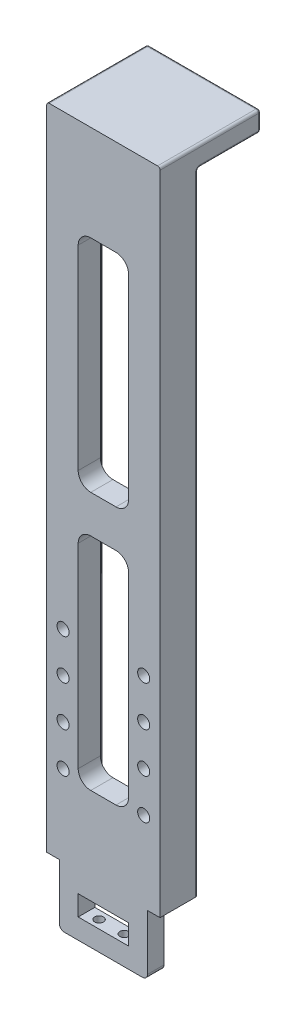
SolidWorks part; units mm, degrees
ref_plane "Ebene vorne" through (0, 0, 0) normal (0, 0, 1) x (1, 0, 0)
ref_plane "Ebene oben" through (0, 0, 0) normal (0, 1, 0) x (1, 0, 0)
ref_plane "Ebene rechts" through (0, 0, 0) normal (1, 0, 0) x (0, 0, -1)
sketch "Skizze1" plane through (0, 0, 0) normal (0, 1, 0) x (1, 0, 0)
  line L0 (-32.248, 0) -> (72.9564, 0) construction
  line L1 (-22.5, 7.5) -> (22.5, 7.5)
  line L2 (-22.5, 7.5) -> (-22.5, -7.5)
  line L3 (-22.5, -7.5) -> (22.5, -7.5)
  line L4 (22.5, 7.5) -> (22.5, -7.5)
  line L5 (0, 40.3012) -> (0, -36.3862) construction
  circle A0 centre (0, 34) radius 32.7
  dimension "D3" = 65.4
  dimension "D1" = 45
  dimension "D2" = 15
  dimension "D4" = 34
extrude "Rundung" add sketch "Skizze1" along normal blind 250 contours A0 L1 L2 L3 L4
sketch "Skizze2" plane through (0, 250, 0) normal (0, 1, 0) x (1, 0, 0)
  line L0 (0, 0) -> (0, 7.7395) construction
  line L1 (-11, 4.5707) -> (11, 4.5707)
  line L2 (-11, 4.5707) -> (-11, 1.3)
  line L3 (-11, 1.3) -> (11, 1.3)
  line L4 (11, 4.5707) -> (11, 1.3)
  line L5 (0, 7.7395) -> (0, -13.5524) construction
  arc A0 (-19.1583, 7.5) -> (19.1583, 7.5) centre (0, 34) ccw construction
  point P7 (0, 1.3)
  dimension "D1" = 22
extrude "AussparungLauf" cut sketch "Skizze2" against normal through all
sketch "Skizze4" plane through (0, 0, -1.3) normal (0, 0, -1) x (-1, 0, 0)
  line L0 (0, 0) -> (0, 250) construction
  line L1 (11, 250) -> (-11, 250) construction
  line L2 (0, 125) -> (27.3493, 125) construction
  line L3 (27.3493, 125) -> (-32.6088, 125) construction
  line L4 (-10, 117.5) -> (10, 117.5)
  line L5 (-10, 220) -> (10, 220)
  line L6 (-10, 220) -> (-10, 132.5)
  line L7 (-10, 132.5) -> (10, 132.5)
  line L8 (10, 220) -> (10, 132.5)
  line L9 (10, 30) -> (10, 117.5)
  line L10 (-10, 30) -> (10, 30)
  line L11 (-10, 30) -> (-10, 117.5)
  dimension "D1" = 20
  dimension "D2" = 30
  dimension "D3" = 7.5
extrude "Schnitt-Linear austragen2" cut sketch "Skizze4" against normal through all
sketch "Skizze5" plane through (0, 0, 7.5) normal (0, 0, 1) x (1, 0, 0)
  line L0 (0, 0) -> (0, 19.9205) construction
  line L1 (-22.5, 0) -> (22.5, 0) construction
  line L2 (-8.4823, 40) -> (10.0951, 40) construction
  circle A0 centre (-16, 32) radius 2.4
  circle A1 centre (16, 32) radius 2.4
  circle A2 centre (16, 48) radius 2.4
  circle A3 centre (16, 64) radius 2.4
  circle A4 centre (16, 80) radius 2.4
  circle A5 centre (-16, 48) radius 2.4
  circle A6 centre (-16, 64) radius 2.4
  circle A7 centre (-16, 80) radius 2.4
  point P8 (-16, 48)
  dimension "D1" = 4.8
  dimension "D2" = 32
  dimension "D3" = 8
  dimension "D4" = 32
  dimension "D5" = 2
  dimension "D6" = 4
extrude "Schnitt-Linear austragen4" cut sketch "Skizze5" against normal blind 6.4
ref_plane "Ebene1" through (0, 0, 1.1) normal (0, 0, 1) x (1, 0, 0)
sketch "Skizze6" plane through (0, 0, 1.1) normal (0, 0, 1) x (1, 0, 0)
  line L0 (-13.6, 32) -> (-18.4, 32) construction
  line L1 (-16, 34.4) -> (-16, 29.6) construction
  circle A0 centre (-16, 32) radius 2.4 construction
  circle A1 centre (-16, 32) radius 2.4 construction
  circle A2 centre (-16, 32) radius 2.85
  circle A3 centre (16, 32) radius 2.85
  circle A4 centre (16, 48) radius 2.85
  circle A5 centre (16, 64) radius 2.85
  circle A6 centre (16, 80) radius 2.85
  circle A7 centre (-16, 48) radius 2.85
  circle A8 centre (-16, 64) radius 2.85
  circle A9 centre (-16, 80) radius 2.85
  dimension "D1" = 5.7
  dimension "D2" = 2
  dimension "D3" = 4
extrude "Schnitt-Linear austragen5" cut sketch "Skizze6" against normal blind 1
sketch "Skizze9" plane through (0, 0, 0) normal (0, -1, 0) x (1, 0, 0)
  line L0 (0, -9.8662) -> (0, 13.0702) construction
  line L1 (-22.5, 7.5) -> (22.5, 7.5) construction
  line L2 (-17.5, 7.5) -> (17.5, 7.5)
  line L3 (-17.5, 7.5) -> (-17.5, 0.8949)
  line L4 (-17.5, 0.8949) -> (17.5, 0.8949)
  line L5 (17.5, 7.5) -> (17.5, 0.8949)
  dimension "D1" = 35
  dimension "D2" = 6.6051
extrude "Aufsatz-Linear austragen1" add sketch "Skizze9" along normal blind 24
sketch "Skizze10" plane through (0, 0, 7.5) normal (0, 0, 1) x (1, 0, 0)
  line L0 (17.5, -24) -> (-17.5, -24) construction
  line L1 (-10, -16) -> (10, -16)
  line L2 (-10, -16) -> (-10, -8)
  line L3 (-10, -8) -> (10, -8)
  line L4 (10, -16) -> (10, -8)
  line L5 (0, 0) -> (0, -29.8897) construction
  dimension "D1" = 8
  dimension "D2" = 20
  dimension "D3" = 8
extrude "Schnitt-Linear austragen7" cut sketch "Skizze10" against normal blind 24
sketch "Skizze11" plane through (0, -24, 0) normal (0, -1, 0) x (1, 0, 0)
  line L0 (0, 0) -> (0, 9.9988) construction
  line L1 (-11.9985, 4.1975) -> (10.6727, 4.1975) construction
  line L2 (17.5, 7.5) -> (-17.5, 7.5) construction
  line L3 (-17.5, 0.8949) -> (17.5, 0.8949) construction
  circle A0 centre (-5, 4.1975) radius 1.75
  circle A1 centre (5, 4.1975) radius 1.75
  dimension "D1" = 3.5
  dimension "D2" = 10
extrude "Schnitt-Linear austragen8" cut sketch "Skizze11" against normal up to next
sketch "Skizze12" plane through (0, 250, 0) normal (0, 1, 0) x (1, 0, 0)
  line L1 (22.5, -7.5) -> (-22.5, -7.5)
  line L2 (22.5, -7.5) -> (22.5, 32.5)
  line L3 (22.5, 32.5) -> (-22.5, 32.5)
  line L4 (-22.5, -7.5) -> (-22.5, 32.5)
  dimension "D1" = 40
extrude "Aufsatz-Linear austragen2" add sketch "Skizze12" along normal blind 8
fillet "Verrundung1" radius 5 8 edges at (-10, 220, 3.1) (10, 220, 3.1) (10, 117.5, 3.1) (-10, 117.5, 3.1) (-10, 30, 3.1) (-10, 132.5, 3.1) (10, 132.5, 3.1) (10, 30, 3.1)
fillet "Verrundung6" radius 1 8 edges at (20.8291, 250, -7.5) (15.2312, 250, -5.0639) (-20.8291, 250, -7.5) (-15.2312, 250, -5.0639) (-11, 250, -2.2528) (0, 250, -1.3) (-11, 125, -3.2057) (11, 250, -2.2528)
fillet "Verrundung7" radius 1 12 edges at (-22.5, 250, -20.5) (-22.5, 249.7071, -7.7929) (22.5, 249.7071, -7.7929) (-22.5, 124.5, -7.5) (22.5, 124.5, -7.5) (-22.5, 258, -12.5) (22.5, 258, -12.5) (22.5, 250, -20.5) (0, 250, -32.5) (0, 258, -32.5) (-22.5, 254, -32.5) (22.5, 254, -32.5)
fillet "Verrundung8" radius 2 2 edges at (17.5, -24, 4.1975) (-17.5, -24, 4.1975)
